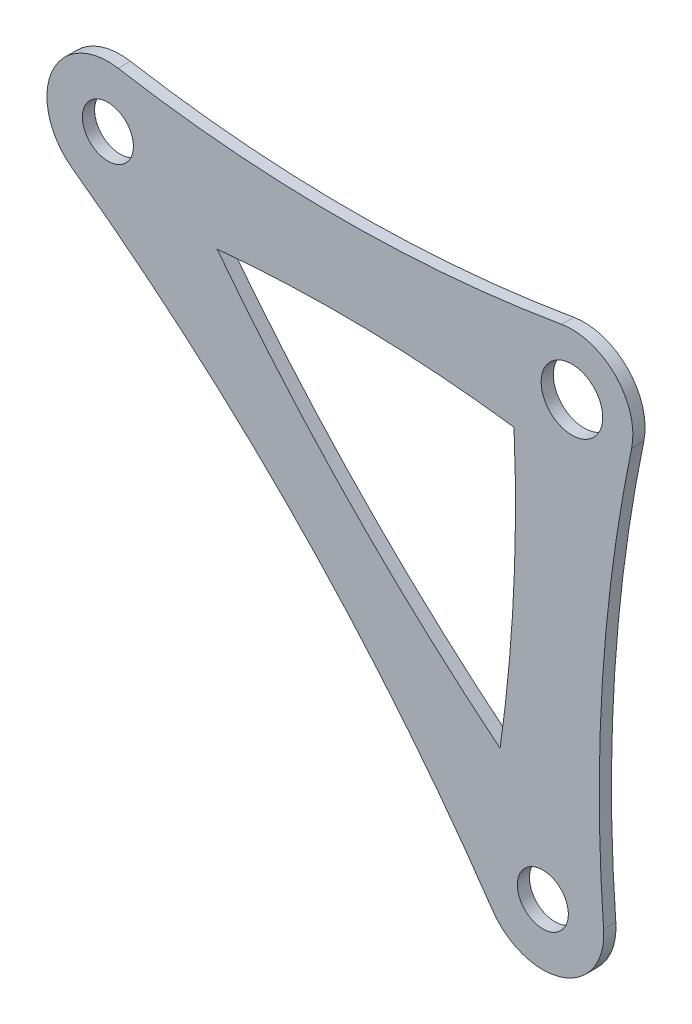
SolidWorks part; units mm, degrees
ref_plane "Plan de face" through (0, 0, 0) normal (1, 0, 0) x (0, 1, 0)
ref_plane "Plan de dessus" through (0, 0, 0) normal (0, 0, 1) x (0, 1, 0)
ref_plane "Plan de droite" through (0, 0, 0) normal (0, 1, 0) x (-1, 0, 0)
sketch "Esquisse1" plane through (0, 0, 0) normal (0, 0, 1) x (0, 1, 0)
  line L0 (0, 0) -> (0, 60.06) construction
  line L1 (0, 60.06) -> (-57.9076, 3.7671) construction
  line L2 (-57.9076, 3.7671) -> (0, 0) construction
  circle A0 centre (-57.9076, 3.7671) radius 3.3
  circle A1 centre (0, 60.06) radius 3.3
  circle A3 centre (-57.9076, 3.7671) radius 7.89
  circle A4 centre (0, 60.06) radius 7.89
  circle A5 centre (0, 0) radius 7.89
  circle A6 centre (0, 0) radius 3.985
  arc A7 (-6.3973, 64.6781) -> (-62.343, 10.2924) centre (-188.8285, 196.3742) cw
  arc A8 (7.7768, 1.3319) -> (7.7768, 58.7281) centre (175.337, 30.03) cw
  arc A9 (-57.3159, -4.1007) -> (-1.6061, -7.7248) centre (-42.3173, -203.5375) cw
  arc A10 (4.4354, 53.5347) -> (-51.5103, -0.851) centre (130.9209, -132.547) ccw
  arc A11 (-56.3015, 11.4919) -> (-0.5917, 7.8678) centre (-15.5903, 207.3046) ccw
  arc A12 (-7.7768, 1.3319) -> (-7.7768, 58.7281) centre (-175.337, 30.03) ccw
  dimension "D4" = 6.6
  dimension "D5" = 7.97
  dimension "D6" = 15.78
  dimension "D7" = 225
  dimension "D8" = 170
  dimension "D9" = 200
  dimension "D1" = 60.06
  dimension "D2" = 80.76
  dimension "D3" = 58.03
extrude "Boss.-Extru.1" add sketch "Esquisse1" along normal blind 1.58 contours A3 A0 | A10 A12 A4 A7 A3 A11 | A11 A3 A10 | A5 A12 A11 A10 A3 A9 | A12 A5 A11 | A5 A6 | A12 A10 A4 | A4 A1 | A12 A11 A5 A8 A4 A10
